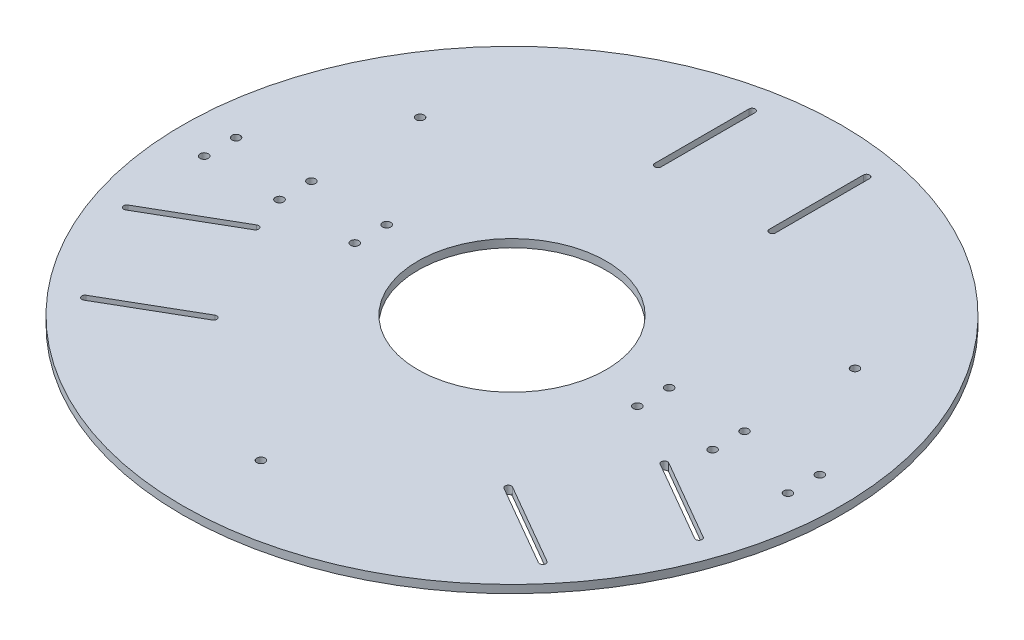
SolidWorks part; units mm, degrees
ref_plane "Front Plane" through (0, 0, 0) normal (0, 0, 1) x (1, 0, 0)
ref_plane "Top Plane" through (0, 0, 0) normal (0, 1, 0) x (1, 0, 0)
ref_plane "Right Plane" through (0, 0, 0) normal (1, 0, 0) x (0, 0, -1)
sketch "Sketch2" plane through (0, 0, 0) normal (0, 1, 0) x (1, 0, 0)
  line L0 (0, 0) -> (0, 262.5) construction
  line L1 (0, 0) -> (-227.3317, 131.25) construction
  line L2 (-45.55, 258.5178) -> (-45.55, 0) construction
  line L3 (-45.55, 236.7757) -> (-45.55, 161.7757) construction
  line L4 (-262.5, -262.5) -> (262.5, -262.5) construction
  line L5 (-262.5, -262.5) -> (-262.5, 262.5) construction
  line L6 (-262.5, 262.5) -> (262.5, 262.5) construction
  line L7 (262.5, -262.5) -> (262.5, 262.5) construction
  line L8 (-43.05, 236.7757) -> (-43.05, 161.7757)
  line L9 (-48.05, 236.7757) -> (-48.05, 161.7757)
  line L10 (45.55, 236.7757) -> (45.55, 161.7757) construction
  line L11 (43.05, 236.7757) -> (43.05, 161.7757)
  line L12 (48.05, 236.7757) -> (48.05, 161.7757)
  line L13 (227.8287, -78.9404) -> (162.8768, -41.4404) construction
  line L14 (226.5787, -81.1054) -> (161.6268, -43.6054)
  line L15 (229.0787, -76.7753) -> (164.1268, -39.2753)
  line L16 (182.2787, -157.8353) -> (117.3268, -120.3353) construction
  line L17 (183.5287, -155.6702) -> (118.5768, -118.1702)
  line L18 (181.0287, -160.0004) -> (116.0768, -122.5004)
  line L19 (-182.2787, -157.8353) -> (-117.3268, -120.3353) construction
  line L20 (-183.5287, -155.6702) -> (-118.5768, -118.1702)
  line L21 (-181.0287, -160.0004) -> (-116.0768, -122.5004)
  line L22 (-227.8287, -78.9404) -> (-162.8768, -41.4404) construction
  line L23 (-226.5787, -81.1054) -> (-161.6268, -43.6054)
  line L24 (-229.0787, -76.7753) -> (-164.1268, -39.2753)
  line L25 (-262.5, 0) -> (262.5, 0)
  circle A0 centre (0, 0) radius 262.5
  circle A1 centre (0, 0) radius 75
  arc A2 (43.05, 236.7757) -> (48.05, 236.7757) centre (45.55, 236.7757) cw
  arc A3 (-43.05, 236.7757) -> (-48.05, 236.7757) centre (-45.55, 236.7757) ccw
  arc A4 (48.05, 161.7757) -> (43.05, 161.7757) centre (45.55, 161.7757) cw
  arc A5 (-48.05, 161.7757) -> (-43.05, 161.7757) centre (-45.55, 161.7757) ccw
  arc A6 (226.5787, -81.1054) -> (229.0787, -76.7753) centre (227.8287, -78.9404) ccw
  arc A7 (164.1268, -39.2753) -> (161.6268, -43.6054) centre (162.8768, -41.4404) ccw
  arc A8 (183.5287, -155.6702) -> (181.0287, -160.0004) centre (182.2787, -157.8353) cw
  arc A9 (116.0768, -122.5004) -> (118.5768, -118.1702) centre (117.3268, -120.3353) cw
  arc A10 (-183.5287, -155.6702) -> (-181.0287, -160.0004) centre (-182.2787, -157.8353) ccw
  arc A11 (-116.0768, -122.5004) -> (-118.5768, -118.1702) centre (-117.3268, -120.3353) ccw
  arc A12 (-226.5787, -81.1054) -> (-229.0787, -76.7753) centre (-227.8287, -78.9404) cw
  arc A13 (-164.1268, -39.2753) -> (-161.6268, -43.6054) centre (-162.8768, -41.4404) cw
  circle A14 centre (-232.5, 12.7) radius 3.2639
  circle A15 centre (-172.5, 12.7) radius 3.2639
  circle A16 centre (-112.5, 12.7) radius 3.2639
  circle A17 centre (112.5, 12.7) radius 3.2639
  circle A18 centre (172.5, 12.7) radius 3.2639
  circle A19 centre (232.5, 12.7) radius 3.2639
  circle A20 centre (232.5, -12.7) radius 3.2639
  circle A21 centre (172.5, -12.7) radius 3.2639
  circle A22 centre (112.5, -12.7) radius 3.2639
  circle A23 centre (-112.5, -12.7) radius 3.2639
  circle A24 centre (-172.5, -12.7) radius 3.2639
  circle A25 centre (-232.5, -12.7) radius 3.2639
  circle A38 centre (-173.2051, 100) radius 3.25
  circle A39 centre (173.2051, 100) radius 3.25
  circle A40 centre (0, -200) radius 3.25
  point P11 (45.55, 199.2757)
  point P15 (-45.55, 199.2757)
  point P34 (149.8028, -139.0853)
  point P35 (195.3528, -60.1904)
  point P48 (-195.3528, -60.1904)
  point P49 (0, 0)
  point P50 (-149.8028, -139.0853)
  point P60 (0, 0)
  point P61 (0, 0)
  point P81 (0, 0)
  point P84 (0, 0)
  point P91 (0, 0)
  dimension "D1" = 525
  dimension "D2" = 45.55
  dimension "D3" = 3
  dimension "D4" = 150
  dimension "D5" = 30
  dimension "D9" = 6.5
  dimension "D13" = 2.5
  dimension "D6" = 6.5278
  dimension "D7" = 236.7757
  dimension "D8" = 60
  dimension "D10" = 200
  dimension "D12" = 75
  dimension "D14" = 12.7
  dimension "D15" = 3
  dimension "D11" = 3
extrude "Boss-Extrude1" add sketch "Sketch2" along normal blind 6.35
